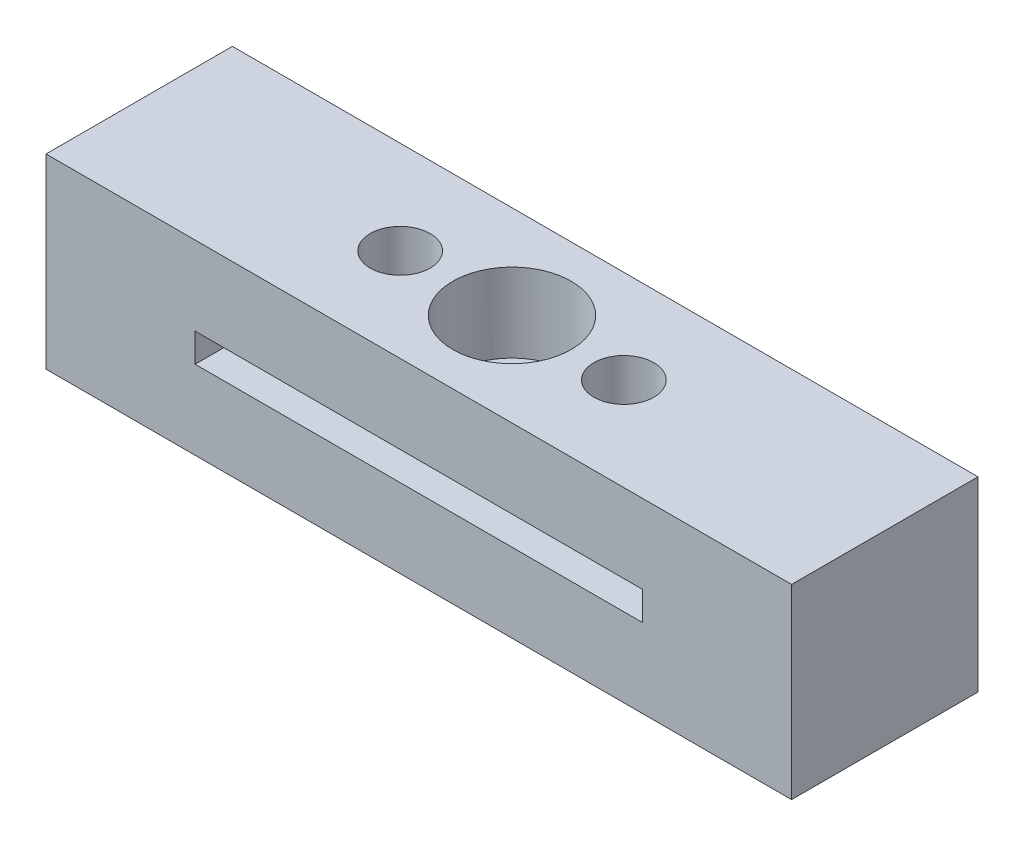
SolidWorks part; units mm, degrees
ref_plane "Front" through (0, 0, 0) normal (0, 0, 1) x (1, 0, 0)
ref_plane "Top" through (0, 0, 0) normal (0, 1, 0) x (1, 0, 0)
ref_plane "Right" through (0, 0, 0) normal (1, 0, 0) x (0, 0, -1)
sketch "Sketch1" plane through (0, 0, 0) normal (0, 0, 1) x (1, 0, 0)
  line L1 (31.75, -7.9375) -> (-31.75, -7.9375)
  line L2 (31.75, -7.9375) -> (31.75, 7.9375)
  line L3 (31.75, 7.9375) -> (-31.75, 7.9375)
  line L4 (-31.75, -7.9375) -> (-31.75, 7.9375)
  line L5 (31.75, -7.9375) -> (-31.75, 7.9375) construction
  line L6 (31.75, 7.9375) -> (-31.75, -7.9375) construction
  line L7 (19.05, -1.2232) -> (-19.05, -1.2232)
  line L8 (19.05, -1.2232) -> (19.05, 1.2232)
  line L9 (19.05, 1.2232) -> (-19.05, 1.2232)
  line L10 (-19.05, -1.2232) -> (-19.05, 1.2232)
  line L11 (19.05, -1.2232) -> (-19.05, 1.2232) construction
  line L12 (19.05, 1.2232) -> (-19.05, -1.2232) construction
  point P0 (0, 0)
  point P6 (0, 0)
  point P11 (0, 0)
  point P12 (0, 0)
  point P13 (0, 0)
  point P14 (0, 0)
  point P15 (0, 0)
  point P16 (0, 0)
  point P17 (0, 0)
  point P18 (0, 0)
  point P19 (0, 0)
  point P20 (31.75, -23.2407)
  point P21 (0, 0)
  point P22 (0, 0)
  point P23 (0, 0)
  dimension "D1" = 15.875
  dimension "D2" = 38.1
  dimension "D3" = 63.5
  dimension "D4" = 2.4463
extrude "Boss-Extrude1" add sketch "Sketch1" along normal mid plane 15.875
hole_wizard "1/4-20 Tapped Hole1" positions "Sketch2" profile "Sketch3" tap size "1/4-20" standard "ANSI Inch" end condition through all
sketch "Sketch2" plane through (0, 7.9375, 0) normal (0, 1, 0) x (1, 0, 0)
  line L1 (0, 0) -> (0, 17.4866) construction
  line L3 (31.75, -7.9375) -> (-31.75, -7.9375) construction
  point P0 (9.525, 0)
  point P2 (-9.525, 0)
  point P13 (-14.9176, 0)
  dimension "D1" = 19.05
  dimension "D2" = 7.9375
sketch "Sketch3" plane through (9.525, 7.9375, 0) normal (1, 0, 0) x (0, 0, 1)
  line L0 (0, 0) -> (0, 15.875)
  line L1 (0, 15.875) -> (2.5527, 15.875)
  line L2 (2.5527, 15.875) -> (2.5527, 0)
  line L5 (2.5527, 0) -> (0, 0)
  line L11 (0, -6.35) -> (0, 107.95) construction
  dimension "Thru Tap Drill Dia." = 5.1054
  dimension "Thru Tap Drill Depth" = 15.875
cosmetic thread "Hole Thread1" parameters "D2"=6.35
cosmetic thread "Hole Thread2" parameters "D2"=6.35
hole_wizard "3/8 Clearance Hole1" positions "Sketch4" profile "Sketch5" hole size "3/8" standard "ANSI Inch" end condition through all
sketch "Sketch4" plane through (0, 7.9375, 0) normal (0, 1, 0) x (1, 0, 0)
  point P0 (0, 0)
sketch "Sketch5" plane through (0, 7.9375, 0) normal (1, 0, 0) x (0, 0, 1)
  line L0 (0, 0) -> (0, 15.875)
  line L1 (0, 15.875) -> (5.0419, 15.875)
  line L2 (5.0419, 15.875) -> (5.0419, 0)
  line L5 (5.0419, 0) -> (0, 0)
  line L11 (0, -6.35) -> (0, 107.95) construction
  dimension "Thru Hole Dia." = 10.0838
  dimension "Thru Hole Depth" = 15.875
